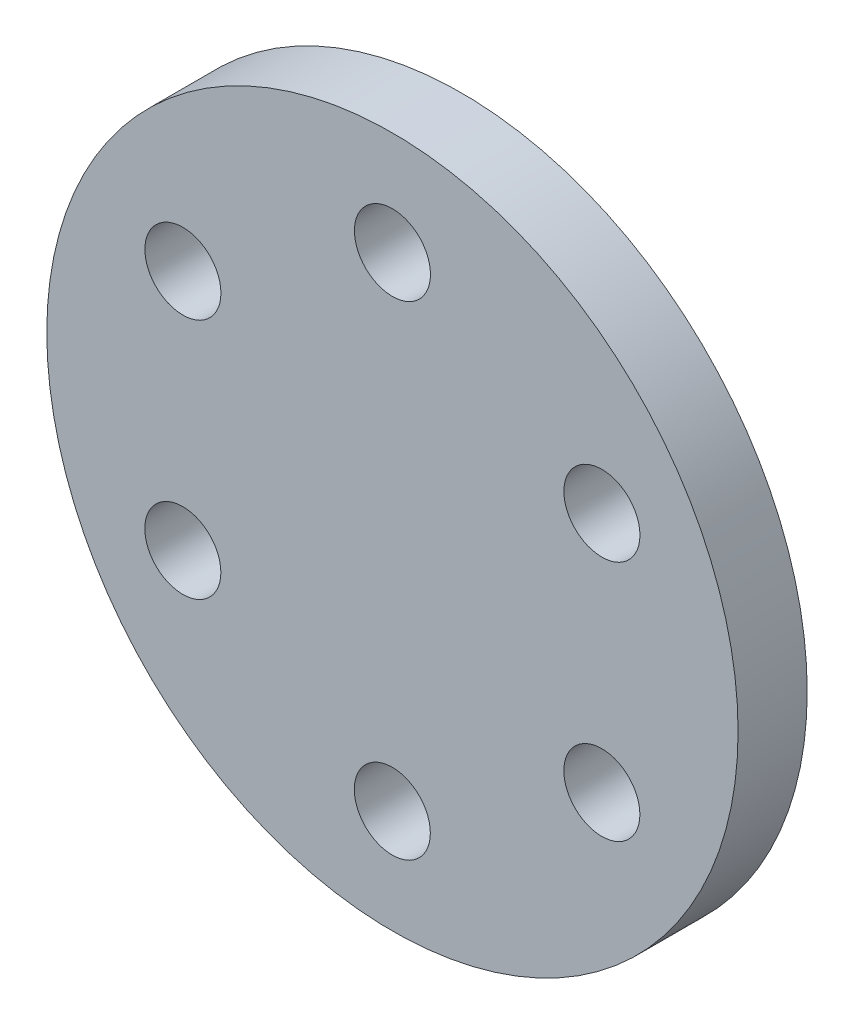
SolidWorks part; units mm, degrees
ref_plane "Plano frontal" through (0, 0, 0) normal (0, 0, 1) x (1, 0, 0)
ref_plane "Plano superior" through (0, 0, 0) normal (0, 1, 0) x (1, 0, 0)
ref_plane "Plano direito" through (0, 0, 0) normal (1, 0, 0) x (0, 0, -1)
sketch "Esboço1" plane through (0, 0, 0) normal (0, 0, 1) x (1, 0, 0)
  circle A0 centre (0, 0) radius 50
  dimension "D1" = 100
extrude "Ressalto-extrusão1" add sketch "Esboço1" along normal blind 10
sketch "Esboço2" plane through (0, 0, 10) normal (0, 0, 1) x (1, 0, 0)
  circle A0 centre (0, 0) radius 35 construction
  circle A1 centre (0, 35) radius 5.5
  circle A2 centre (30.3021, 17.4949) radius 5.5
  circle A3 centre (30.2933, -17.5) radius 5.5
  circle A4 centre (-0.0176, -34.9898) radius 5.5
  circle A5 centre (-30.3197, -17.4847) radius 5.5
  circle A6 centre (-30.3109, 17.5102) radius 5.5
  point P18 (-0.0088, 0.0051)
  dimension "D1" = 70
  dimension "D2" = 11
  dimension "D3" = 6
extrude "Corte-extrusão1" cut sketch "Esboço2" against normal through all
